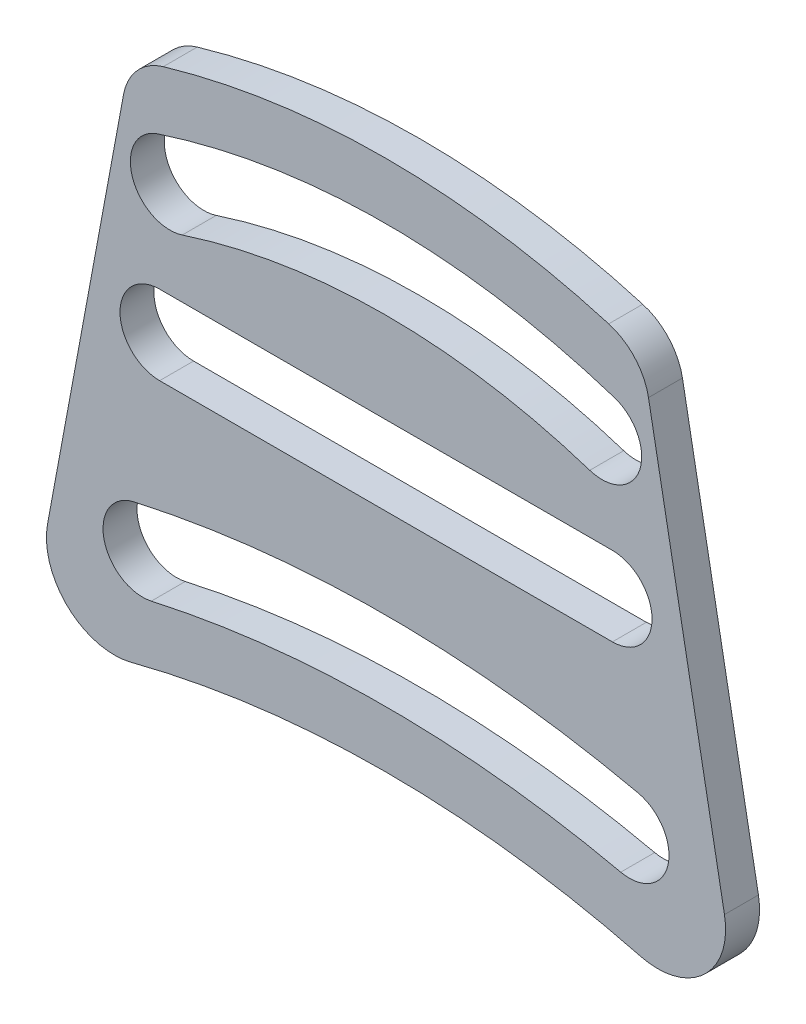
SolidWorks part; units mm, degrees
ref_plane "Płaszczyzna przednia" through (0, 0, 0) normal (0, 0, 1) x (1, 0, 0)
ref_plane "Płaszczyzna górna" through (0, 0, 0) normal (0, 1, 0) x (1, 0, 0)
ref_plane "Płaszczyzna prawa" through (0, 0, 0) normal (1, 0, 0) x (0, 0, -1)
sketch "Sketch1" plane through (0, 0, 0) normal (0, 0, 1) x (1, 0, 0)
  line L0 (0, -194.6641) -> (0, 79.3679) construction
  line L1 (-20, -14.0369) -> (20, -14.0208)
  line L3 (-20, -21.0369) -> (20, -21.0208)
  line L6 (-29.8994, -36.9349) -> (-23.1871, -0.7379)
  line L9 (29.8994, -36.9349) -> (23.1871, -0.7379)
  arc A0 (-20, -14.0369) -> (-20, -21.0369) centre (-20, -17.5369) ccw
  arc A1 (20, -21.0208) -> (20, -14.0208) centre (20, -17.5208) ccw
  arc A2 (-19.0864, -5.5655) -> (19.0864, -5.5655) centre (0, -64.0289) cw construction
  arc A11 (20.1726, -2.2384) -> (-20.1726, -2.2384) centre (0, -64.0289) ccw
  arc A16 (18.0002, -8.8927) -> (-18.0002, -8.8927) centre (0, -64.0289) ccw
  arc A17 (18.0002, -8.8927) -> (20.1726, -2.2384) centre (19.0864, -5.5655) ccw
  arc A18 (-20.1726, -2.2384) -> (-18.0002, -8.8927) centre (-19.0864, -5.5655) ccw
  arc A19 (-19.6764, 3.1488) -> (19.6764, 3.1488) centre (0, -64.0289) cw
  arc A20 (-21.5, -34.8555) -> (21.5, -34.8555) centre (0, -130.9805) cw construction
  arc A21 (22.264, -31.4399) -> (-22.264, -31.4399) centre (0, -130.9805) ccw
  arc A22 (20.736, -38.2711) -> (-20.736, -38.2711) centre (0, -130.9805) ccw
  arc A23 (20.736, -38.2711) -> (22.264, -31.4399) centre (21.5, -34.8555) ccw
  arc A24 (-22.264, -31.4399) -> (-20.736, -38.2711) centre (-21.5, -34.8555) ccw
  arc A25 (-22.5, -43.8383) -> (22.5, -43.8383) centre (0, -130.9805) cw
  arc A26 (19.6764, 3.1488) -> (23.1871, -0.7379) centre (18.2709, -1.6496) cw
  arc A27 (-19.6764, 3.1488) -> (-23.1871, -0.7379) centre (-18.2709, -1.6496) ccw
  arc A28 (22.5, -43.8383) -> (29.8994, -36.9349) centre (24, -38.0289) ccw
  arc A29 (-22.5, -43.8383) -> (-29.8994, -36.9349) centre (-24, -38.0289) cw
  point P1 (0, 0)
  point P13 (0, -2.5289)
  point P18 (0, 5.9711)
  point P22 (22.4136, -6.6518)
  point P23 (0, -32.4805)
  point P31 (-26.2636, 12.5595)
  point P39 (-32.9827, -28.1931)
  point P40 (-31.258, -25.645)
  dimension "D1" = 7
  dimension "D2" = 61.5
  dimension "D3" = 47
  dimension "D4" = 7
  dimension "D5" = 45
  dimension "D6" = 70
  dimension "D8" = 5
  dimension "D9" = 7
  dimension "D10" = 90
  dimension "D11" = 5
  dimension "D12" = 50
  dimension "D13" = 5
  dimension "D14" = 6
  dimension "D15" = 50
  dimension "D16" = 60
  dimension "D7" = 20
extrude "Boss-Extrude4" add sketch "Sketch1" along normal blind 3 contours A21 A24 A22 A23 | A29 A25 A28 L9 A26 A19 A27 L6 A24 A21 A23 A22 A18 A11 A17 A16 A1 L3 A0 L1
